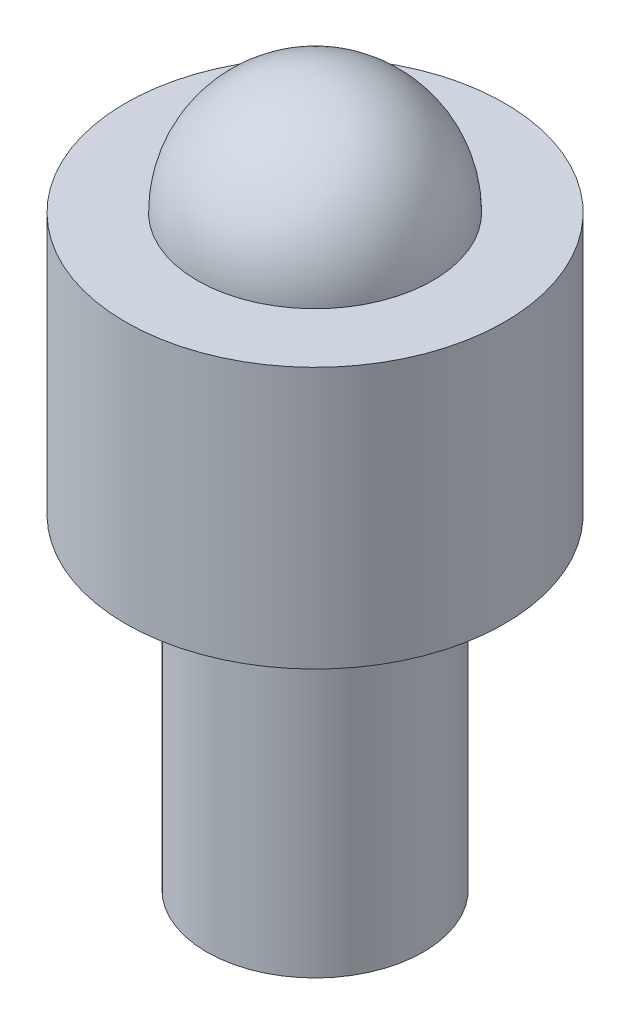
SolidWorks part; units mm, degrees
material "尼龙 6/10"
ref_plane "前视基准面" through (0, 0, 0) normal (0, 0, 1) x (1, 0, 0)
ref_plane "上视基准面" through (0, 0, 0) normal (0, 1, 0) x (1, 0, 0)
ref_plane "右视基准面" through (0, 0, 0) normal (1, 0, 0) x (0, 0, -1)
sketch "草图1" plane through (0, 0, 0) normal (0, 1, 0) x (1, 0, 0)
  circle A0 centre (0, 0) radius 4
extrude "凸台-拉伸1" add sketch "草图1" along normal blind 12
sketch "草图2" plane through (0, 12, 0) normal (0, 1, 0) x (1, 0, 0)
  circle A0 centre (0, 0) radius 7
extrude "凸台-拉伸2" add sketch "草图2" along normal blind 9.65
sketch "草图3" plane through (0, 21.65, 0) normal (0, 1, 0) x (1, 0, 0)
  line L0 (0, 4.35) -> (0, -4.35)
  arc A0 (0, -4.35) -> (0, 4.35) centre (0, 0) ccw
revolve "旋转1" add sketch "草图3" angle 360 about L0
